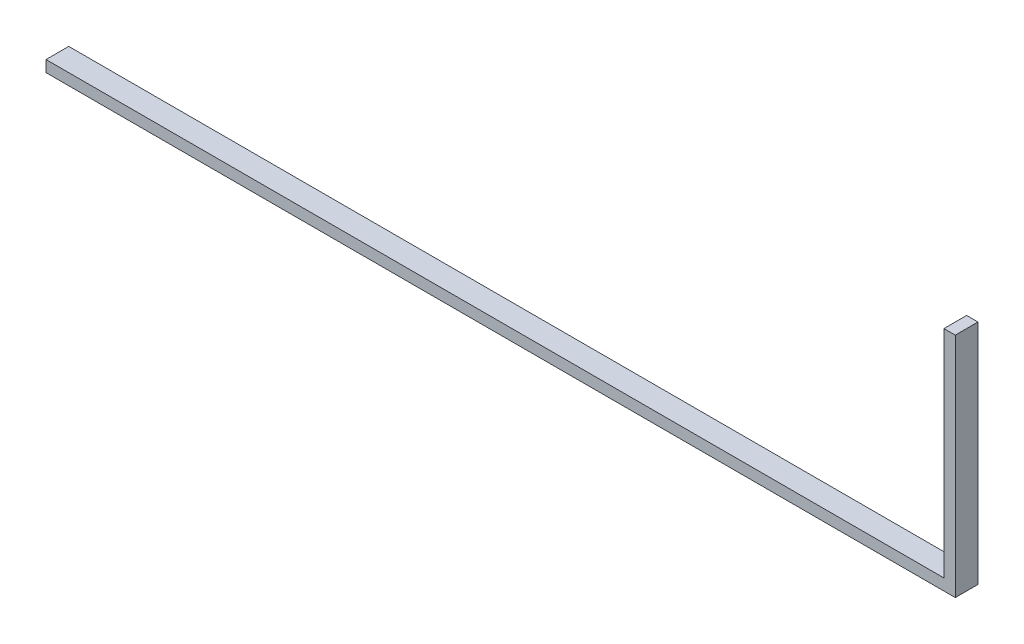
SolidWorks part; units mm, degrees
ref_plane "前视基准面" through (0, 0, 0) normal (0, 0, 1) x (1, 0, 0)
ref_plane "上视基准面" through (0, 0, 0) normal (0, 1, 0) x (1, 0, 0)
ref_plane "右视基准面" through (0, 0, 0) normal (1, 0, 0) x (0, 0, -1)
sketch "草图1" plane through (0, 0, 0) normal (0, 0, 1) x (1, 0, 0)
  line L0 (0, 0) -> (4000, 0)
  line L1 (4000, 0) -> (4000, 1000)
  line L2 (4000, 1000) -> (3950, 1000)
  line L3 (3950, 1000) -> (3950, 50)
  line L4 (3950, 50) -> (0, 50)
  line L5 (0, 50) -> (0, 0)
  dimension "D1" = 50
  dimension "D2" = 50
  dimension "D3" = 4000
  dimension "D4" = 1000
extrude "凸台-拉伸1" add sketch "草图1" along normal blind 100
